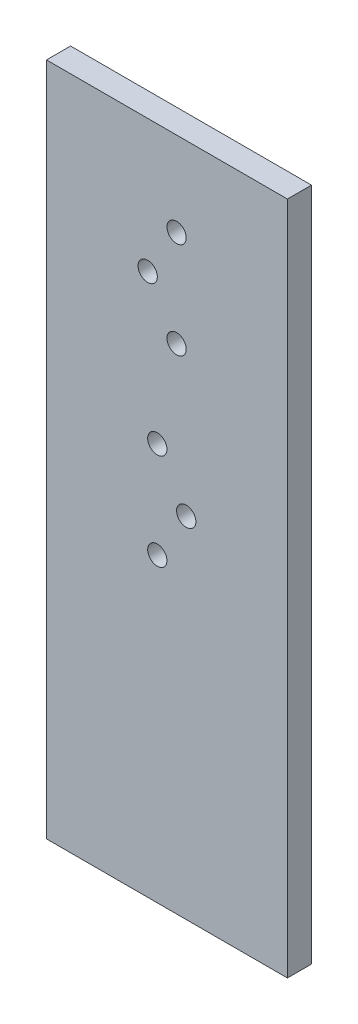
SolidWorks part; units mm, degrees
ref_plane "前视" through (0, 0, 0) normal (0, 0, 1) x (1, 0, 0)
ref_plane "上视" through (0, 0, 0) normal (0, 1, 0) x (1, 0, 0)
ref_plane "右视" through (0, 0, 0) normal (1, 0, 0) x (0, 0, -1)
sketch "草图1" plane through (0, 0, 0) normal (0, 0, 1) x (1, 0, 0)
  line L1 (25, -70) -> (-25, -70)
  line L2 (25, -70) -> (25, 70)
  line L3 (25, 70) -> (-25, 70)
  line L4 (-25, -70) -> (-25, 70)
  line L5 (25, -70) -> (-25, 70) construction
  line L6 (25, 70) -> (-25, -70) construction
  point P0 (0, 0)
  dimension "D1" = 140
  dimension "D2" = 50
extrude "凸台-拉伸1" add sketch "草图1" along normal blind 5
sketch "草图2" plane through (0, 0, 5) normal (0, 0, 1) x (1, 0, 0)
  line L0 (25, -70) -> (25, 70) construction
  line L1 (-15, 15) -> (10, 15) construction
  line L2 (-15, 0) -> (-15, -35) construction
  line L3 (9.4949, -10) -> (10, -10) construction
  line L4 (10, 15) -> (10, -10) construction
  line L5 (25, 70) -> (-25, 70) construction
  line L6 (15, 25) -> (-10, 25) construction
  line L7 (15, 25) -> (15, 60) construction
  line L8 (15, 60) -> (-10, 60) construction
  line L9 (-10, 25) -> (-10, 60) construction
  line L11 (-20, 2.5) -> (10, 2.5) construction
  line L12 (15, 42.5) -> (-10, 42.5) construction
  line L13 (-25, 70) -> (-25, -70) construction
  circle A0 centre (-2, 12.5) radius 2
  circle A1 centre (-2, -7.5) radius 2
  circle A2 centre (4, 2.5) radius 2
  circle A3 centre (2, 52.5) radius 2
  circle A4 centre (2, 32.5) radius 2
  circle A5 centre (-4, 42.5) radius 2
  dimension "D10" = 4
  dimension "D11" = 4
  dimension "D12" = 4
  dimension "D15" = 4
  dimension "D16" = 4
  dimension "D17" = 4
  dimension "D1" = 35
  dimension "D2" = 25
  dimension "D3" = 10
  dimension "D4" = 35
  dimension "D5" = 25
  dimension "D6" = 10
  dimension "D7" = 13
  dimension "D8" = 13
  dimension "D9" = 6
  dimension "D13" = 10
  dimension "D14" = 10
  dimension "D18" = 10
  dimension "D19" = 10
  dimension "D20" = 13
  dimension "D21" = 13
  dimension "D22" = 6
  dimension "D23" = 10
  dimension "D24" = 25
  dimension "D25" = 10
extrude "切除-拉伸1" cut sketch "草图2" against normal blind 5
sketch "草图3" plane through (0, 0, 0) normal (0, 0, -1) x (-1, 0, 0)
  line L0 (0, -70) -> (0, 70)
  line L1 (25, -70) -> (-25, -70) construction
  line L2 (-25, 70) -> (25, 70) construction
sketch "草图4" plane through (0, 0, 5) normal (0, 0, 1) x (1, 0, 0)
  line L0 (0, -70) -> (0, 70)
  line L1 (-25, -70) -> (25, -70) construction
  line L2 (25, 70) -> (-25, 70) construction
